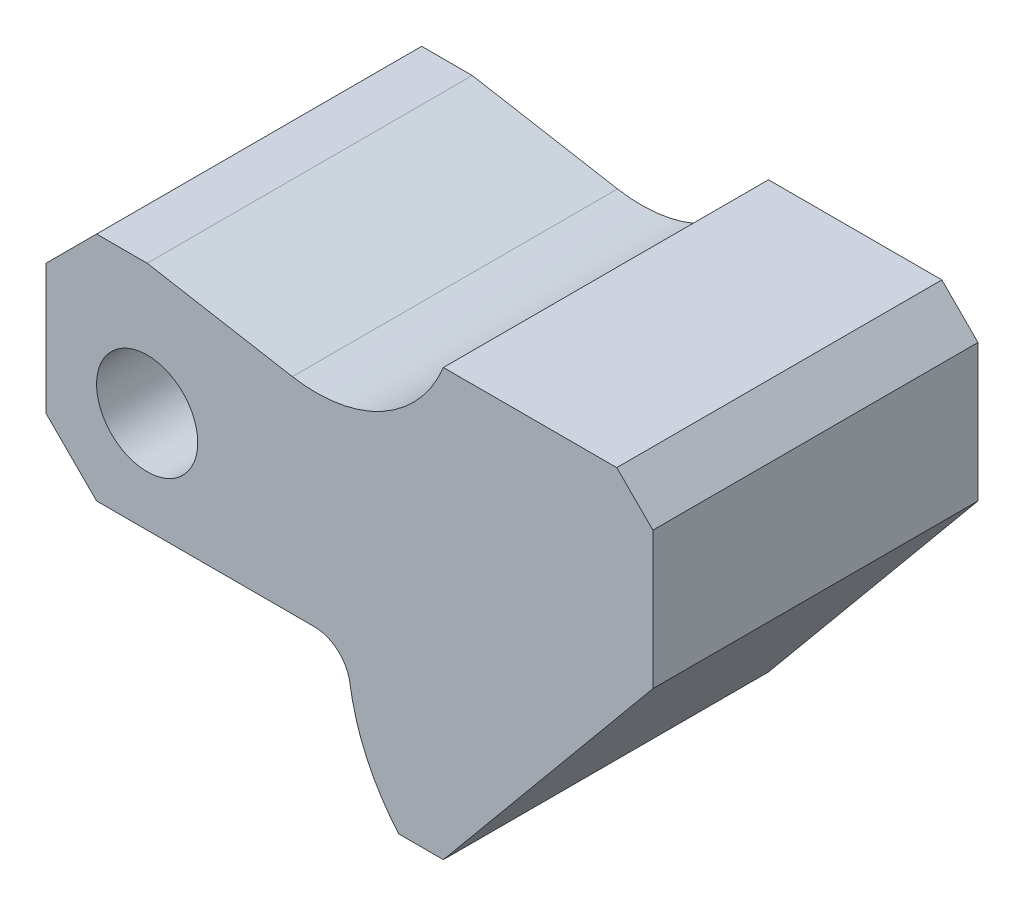
SolidWorks part; units mm, degrees
material "AISI 1020"
ref_plane "Front Plane" through (0, 0, 0) normal (0, 0, 1) x (1, 0, 0)
ref_plane "Top Plane" through (0, 0, 0) normal (0, 1, 0) x (1, 0, 0)
ref_plane "Right Plane" through (0, 0, 0) normal (1, 0, 0) x (0, 0, -1)
sketch "Esquisse1" plane through (0, 0, 0) normal (0, 0, 1) x (1, 0, 0)
  line L0 (0, 0) -> (6.166, 0)
  line L1 (6.166, 0) -> (35.166, 35)
  line L2 (35.166, 35) -> (35.166, 54)
  line L3 (35.166, 54) -> (30.166, 59)
  line L4 (30.166, 59) -> (6.166, 59)
  line L11 (-14.7299, 47.4551) -> (-34.834, 51)
  line L12 (-34.834, 51) -> (-41.834, 51)
  line L13 (-41.834, 51) -> (-48.834, 44)
  line L14 (-48.834, 44) -> (-48.834, 26)
  line L15 (-48.834, 26) -> (-41.834, 19)
  line L16 (-41.834, 19) -> (-11.7214, 19)
  arc A3 (6.166, 59) -> (-14.7299, 47.4551) centre (-11.4306, 66.1665) cw
  arc A4 (-11.7214, 19) -> (-6.7758, 14.7353) centre (-11.7214, 14) cw
  arc A5 (-6.7758, 14.7353) -> (0, 0) centre (21.9089, 19) ccw
  point P32 (3.083, 0)
  dimension "D8" = 19
  dimension "D17" = 5
  dimension "D18" = 29
  dimension "D1" = 59
  dimension "D2" = 5
  dimension "D3" = 45
  dimension "D4" = 29
  dimension "D5" = 24
  dimension "D6" = 29
  dimension "D7" = 84
  dimension "D9" = 10
  dimension "D10" = 7
  dimension "D11" = 45
  dimension "D12" = 14
  dimension "D14" = 7
  dimension "D15" = 45
  dimension "D16" = 19
  dimension "D19" = 19
  dimension "D13" = 32
extrude "Boss.-Extru.1" add sketch "Esquisse1" along normal mid plane 45
sketch "Esquisse2" plane through (0, 0, 22.5) normal (0, 0, 1) x (1, 0, 0)
  line L0 (-48.834, 44) -> (-48.834, 26) construction
  line L1 (-41.834, 19) -> (-11.7214, 19) construction
  circle A0 centre (-34.834, 33) radius 7
  dimension "D1" = 14
  dimension "D2" = 14
  dimension "D3" = 14
extrude "Enlèv. mat.-Extru.1" cut sketch "Esquisse2" against normal through all
equation "\"A\"= 84"
equation "\"B\"= 59"
equation "\"C\"= 45"
equation "\"D1@Esquisse1\"=\"B\""
equation "\"D7@Esquisse1\"=\"A\""
equation "\"D1@Boss.-Extru.1\"=\"C\""
